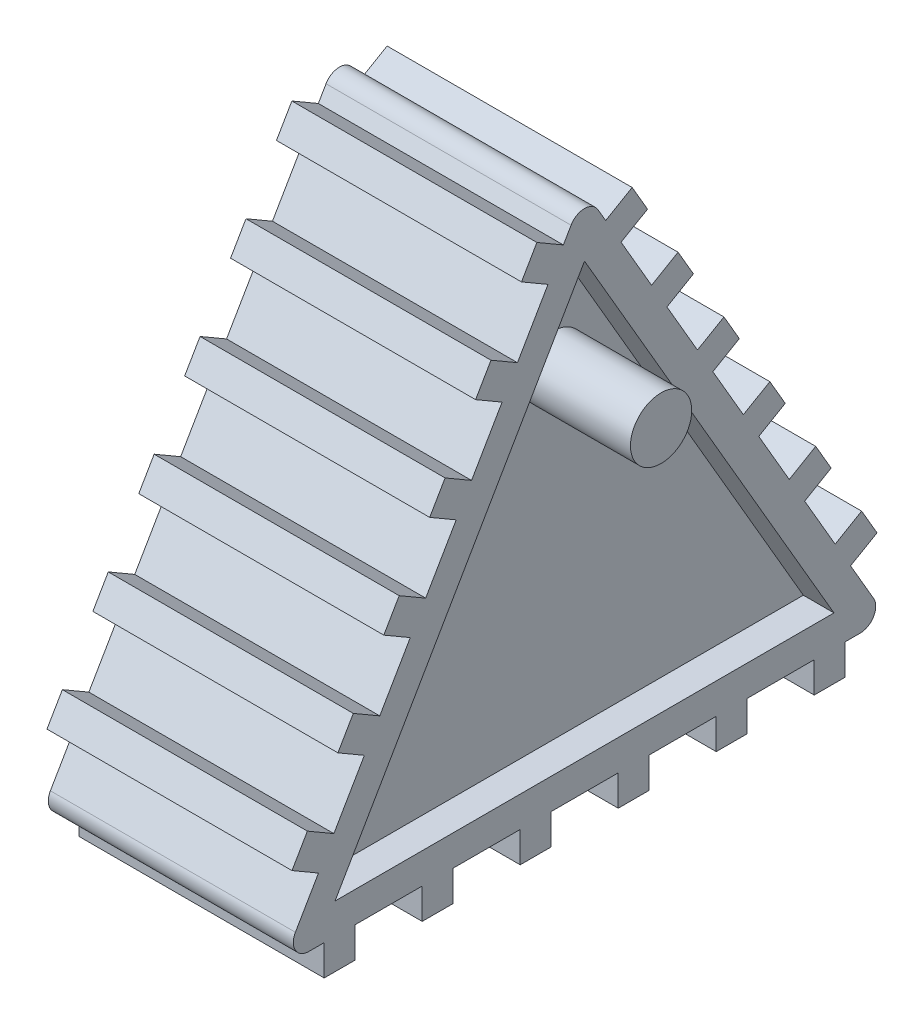
SolidWorks part; units mm, degrees
ref_plane "Front Plane" through (0, 0, 0) normal (0, 0, 1) x (1, 0, 0)
ref_plane "Top Plane" through (0, 0, 0) normal (0, 1, 0) x (1, 0, 0)
ref_plane "Right Plane" through (0, 0, 0) normal (1, 0, 0) x (0, 0, -1)
sketch "Sketch1" plane through (0, 0, 0) normal (1, 0, 0) x (0, 0, -1)
  line L0 (-23.9253, -38.6951) -> (21.0747, 38.7649)
  line L1 (-26.1421, 42.5454) -> (72.6841, 42.5454)
  line L2 (-26.1421, 42.5454) -> (-26.1421, -42.5111)
  line L3 (-21.729, -42.5111) -> (68.271, -42.5111)
  line L4 (72.6841, 42.5454) -> (72.6841, -42.5111)
  line L5 (25.4673, 38.7649) -> (70.4673, -38.6951)
  arc A0 (21.0747, 38.7649) -> (25.4673, 38.7649) centre (23.271, 37.4889) cw
  arc A1 (68.271, -42.5111) -> (70.4673, -38.6951) centre (68.271, -39.9711) ccw
  arc A2 (-21.729, -42.5111) -> (-23.9253, -38.6951) centre (-21.729, -39.9711) cw
  point P7 (23.271, 42.5454)
  dimension "D1" = 2.54
  dimension "D2" = 2.54
  dimension "D3" = 90
  dimension "D4" = 80
extrude "Boss-Extrude2" add sketch "Sketch1" along normal blind 40 contours L5 A1 L3 A2 L0 A0
shell "Shell8" thickness 5
shell "Shell9" thickness 5
sketch "Sketch2" plane through (35, 0, 0) normal (1, 0, 0) x (0, 0, -1)
  circle A0 centre (23.271, 15.2251) radius 5
extrude "Boss-Extrude3" add sketch "Sketch2" along normal blind 17.5
sketch "Sketch5" plane through (0, 20.8435, -35.8786) normal (0, 0.5023, -0.8647) x (-1, 0, 0)
  line L0 (-40, 20.7261) -> (-40, -68.8566) construction
  line L1 (-40, 18.2261) -> (0, 18.2261)
  line L2 (-40, 18.2261) -> (-40, 13.2261)
  line L3 (-40, 13.2261) -> (0, 13.2261)
  line L4 (0, 18.2261) -> (0, 13.2261)
  line L5 (0, 20.7261) -> (0, -68.8566) construction
  line L6 (-40, 20.7261) -> (0, 20.7261) construction
  dimension "D1" = 2.5
  dimension "D2" = 5
extrude "Boss-Extrude4" add sketch "Sketch5" along normal blind 5
pattern_linear "LPattern4" count 6 spacing 14.9165 along (0, -0.8647, -0.5023) of "Boss-Extrude4"
sketch "Sketch10" plane through (0, 0.6279, 1.0808) normal (0, 0.5023, 0.8647) x (1, 0, 0)
  line L0 (0, -45.4771) -> (0, 44.1055) construction
  line L1 (0, 41.6055) -> (40, 41.6055)
  line L2 (0, 41.6055) -> (0, 36.6055)
  line L3 (0, 36.6055) -> (40, 36.6055)
  line L4 (40, 41.6055) -> (40, 36.6055)
  line L5 (40, -45.4771) -> (40, 44.1055) construction
  line L6 (40, 44.1055) -> (0, 44.1055) construction
  dimension "D1" = 2.5
  dimension "D2" = 5
extrude "Boss-Extrude5" add sketch "Sketch10" along normal blind 5
pattern_linear "LPattern5" count 6 spacing 14.9165 along (0, -0.8647, 0.5023) of "Boss-Extrude5"
sketch "Sketch11" plane through (0, -42.5111, 0) normal (0, -1, 0) x (1, 0, 0)
  line L0 (0, 21.729) -> (0, -68.271) construction
  line L1 (0, 19.229) -> (40, 19.229)
  line L2 (0, 19.229) -> (0, 14.229)
  line L3 (0, 14.229) -> (40, 14.229)
  line L4 (40, 19.229) -> (40, 14.229)
  line L5 (40, 21.729) -> (40, -68.271) construction
  line L6 (40, 21.729) -> (0, 21.729) construction
  dimension "D1" = 5
  dimension "D2" = 2.5
extrude "Boss-Extrude6" add sketch "Sketch11" along normal blind 5
pattern_linear "LPattern8" count 6 spacing 16 along (0, 0, -1) of "Boss-Extrude6"
ref_plane "Plane1" through (65, 0, 0) normal (1, 0, 0) x (0, 0, -1)
